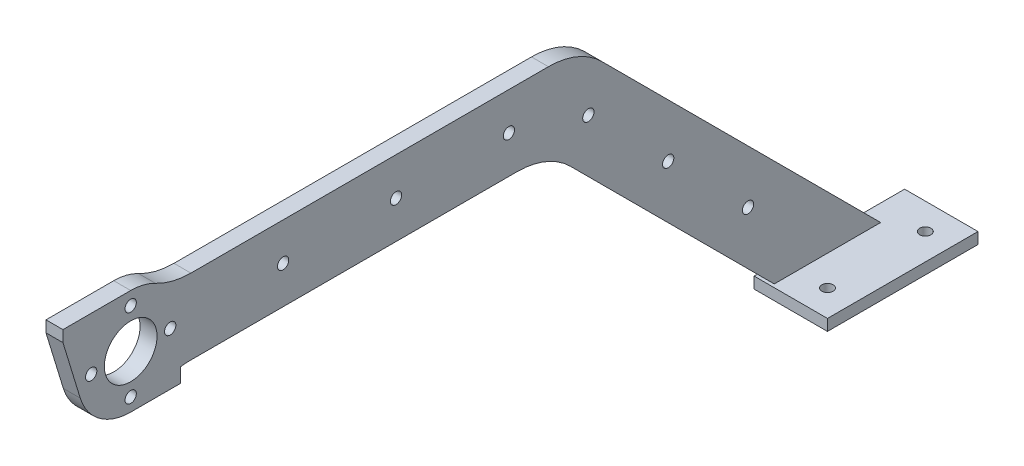
SolidWorks part; units mm, degrees
ref_plane "前视基准面" through (0, 0, 0) normal (0, 0, 1) x (1, 0, 0)
ref_plane "上视基准面" through (0, 0, 0) normal (0, 1, 0) x (1, 0, 0)
ref_plane "右视基准面" through (0, 0, 0) normal (1, 0, 0) x (0, 0, -1)
sketch "草图1" plane through (0, 0, 0) normal (1, 0, 0) x (0, 0, -1)
  line L2 (116.8579, -15.8579) -> (171, -70)
  line L3 (171, -70) -> (199.2843, -70)
  line L4 (199.2843, -70) -> (125.1421, 4.1421)
  line L5 (111, 10) -> (16, 10)
  line L7 (16, -10) -> (102.7369, -10)
  line L8 (186.193, -71.0509) -> (123.8062, -8.664) construction
  line L9 (0, 14) -> (-18, 14)
  line L10 (-18, 14) -> (-18, 11)
  line L11 (-18, 11) -> (-13.3889, -4.091)
  line L12 (13.2242, -14) -> (13.2242, -10)
  line L13 (0, -14) -> (13.2242, -14)
  arc A0 (6.5882, 12.3529) -> (6.5882, -12.3529) centre (0, 0) ccw
  circle A1 centre (0, 0) radius 10.5 construction
  circle A2 centre (0, 0) radius 7
  circle A3 centre (0, 10.5) radius 1.5
  circle A4 centre (10.5, 0) radius 1.5
  circle A5 centre (0, -10.5) radius 1.5
  circle A6 centre (-10.5, 0) radius 1.5
  arc A7 (125.1421, 4.1421) -> (111, 10) centre (111, -10) ccw
  arc A8 (102.7369, -10) -> (116.8579, -15.8579) centre (102.7157, -30) cw
  circle A9 centre (40.5, 0) radius 1.5
  circle A10 centre (70.5, 0) radius 1.5
  circle A11 centre (100.5, 0) radius 1.5
  circle A12 centre (121.61, -6.4679) radius 1.5
  circle A13 centre (142.8232, -27.6811) radius 1.5
  circle A14 centre (164.0364, -48.8943) radius 1.5
  arc A15 (16, 10) -> (6.5882, 12.3529) centre (16, 30) cw
  arc A16 (16, -10) -> (6.5882, -12.3529) centre (16, -30) ccw
  point P36 (185.1421, -70)
  point P43 (9.798, 7.7889)
  point P50 (9.798, -10)
  dimension "D1" = 28
  dimension "D2" = 21
  dimension "D3" = 14
  dimension "D4" = 3
  dimension "D9" = 20
  dimension "D13" = 3
  dimension "D16" = 30
  dimension "D17" = 3
  dimension "D19" = 30
  dimension "D24" = 20
  dimension "D25" = 20
  dimension "D6" = 135
  dimension "D7" = 20
  dimension "D8" = 171
  dimension "D10" = 70
  dimension "D11" = 20
  dimension "D14" = 40.5
  dimension "D18" = 21.11
  dimension "D20" = 30
  dimension "D21" = 18
  dimension "D22" = 3
  dimension "D26" = 13.2242
  dimension "D28" = 20
  dimension "D15" = 3
  dimension "D5" = 4
extrude "凸台-拉伸1" add sketch "草图1" along normal mid plane 4.5
sketch "草图5" plane through (0, -70, 0) normal (0, -1, 0) x (1, 0, 0)
  line L0 (-2.25, -116.8579) -> (-2.25, -171) construction
  line L1 (-2.25, -170.1443) -> (17.25, -170.1443)
  line L2 (-2.25, -170.1443) -> (-2.25, -210.1443)
  line L3 (-2.25, -210.1443) -> (17.25, -210.1443)
  line L4 (17.25, -170.1443) -> (17.25, -210.1443)
  line L5 (2.25, -199.2843) -> (-2.25, -199.2843) construction
  dimension "D1" = 19.5
  dimension "D2" = 40
  dimension "D3" = 10.86
extrude "凸台-拉伸3" add sketch "草图5" along normal blind 3
sketch "草图6" plane through (0, -70, 0) normal (0, 1, 0) x (1, 0, 0)
  line L0 (17.25, 190.1443) -> (-2.25, 190.1443) construction
  line L1 (17.25, 210.1443) -> (17.25, 170.1443) construction
  line L2 (-2.25, 199.2843) -> (-2.25, 125.1421) construction
  line L3 (-2.25, 210.1443) -> (17.25, 210.1443) construction
  circle A0 centre (10.25, 203.1443) radius 1.5
  circle A1 centre (10.25, 177.1443) radius 1.5
  dimension "D3" = 3
  dimension "D1" = 7
  dimension "D2" = 7
extrude "切除-拉伸2" cut sketch "草图6" against normal through all
